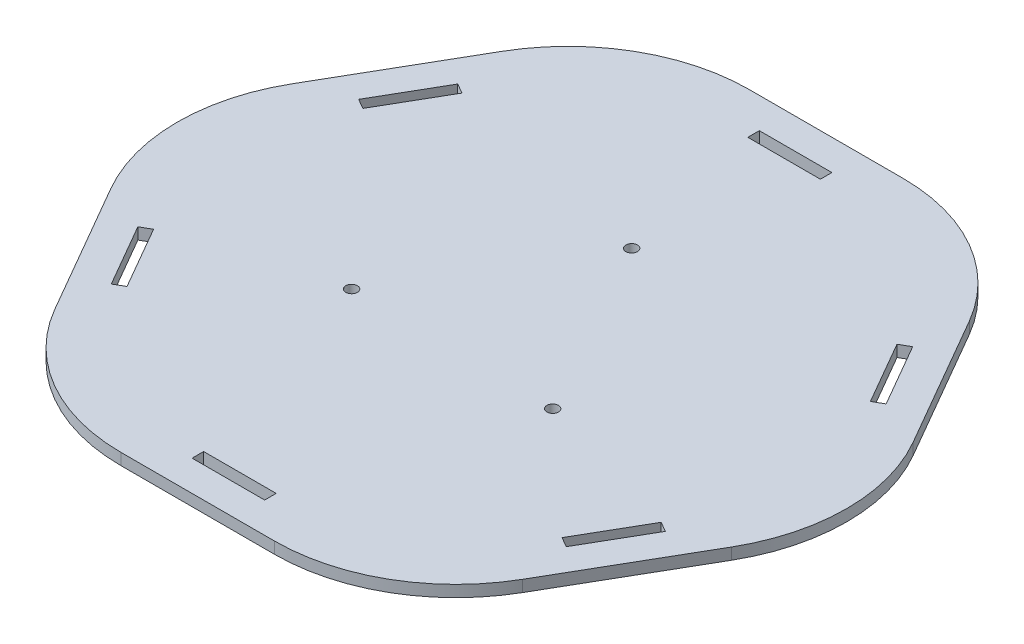
SolidWorks part; units mm, degrees
material "Acrylic (Medium-high impact)"
ref_plane "Front Plane" through (0, 0, 0) normal (0, 0, 1) x (1, 0, 0)
ref_plane "Top Plane" through (0, 0, 0) normal (0, 1, 0) x (1, 0, 0)
ref_plane "Right Plane" through (0, 0, 0) normal (1, 0, 0) x (0, 0, -1)
sketch "Sketch1" plane through (0, 0, 0) normal (0, 1, 0) x (1, 0, 0)
  line L0 (0, 0) -> (200, 0)
  line L1 (171.1325, 50) -> (128.8675, 123.2051)
  line L2 (42.265, 173.2051) -> (-42.265, 173.2051)
  line L3 (-128.8675, 123.2051) -> (-171.1325, 50)
  line L4 (-171.1325, -50) -> (-128.8675, -123.2051)
  line L5 (-42.265, -173.2051) -> (42.265, -173.2051)
  line L6 (128.8675, -123.2051) -> (171.1325, -50)
  line L8 (-20, -150) -> (20, -150)
  line L9 (-20, -150) -> (-20, -156.35)
  line L10 (-20, -156.35) -> (20, -156.35)
  line L11 (20, -150) -> (20, -156.35)
  line L12 (0, -55) -> (0, 55) construction
  line L13 (-55, 0) -> (55, 0) construction
  line L14 (-139.9038, -57.6795) -> (-145.4031, -60.8545)
  line L15 (-139.9038, -57.6795) -> (-119.9038, -92.3205)
  line L16 (-119.9038, -92.3205) -> (-125.4031, -95.4955)
  line L17 (-145.4031, -60.8545) -> (-125.4031, -95.4955)
  line L18 (-119.9038, 92.3205) -> (-125.4031, 95.4955)
  line L19 (-119.9038, 92.3205) -> (-139.9038, 57.6795)
  line L20 (-139.9038, 57.6795) -> (-145.4031, 60.8545)
  line L21 (-125.4031, 95.4955) -> (-145.4031, 60.8545)
  line L22 (20, 150) -> (20, 156.35)
  line L23 (20, 150) -> (-20, 150)
  line L24 (-20, 150) -> (-20, 156.35)
  line L25 (20, 156.35) -> (-20, 156.35)
  line L26 (139.9038, 57.6795) -> (145.4031, 60.8545)
  line L27 (139.9038, 57.6795) -> (119.9038, 92.3205)
  line L28 (119.9038, 92.3205) -> (125.4031, 95.4955)
  line L29 (145.4031, 60.8545) -> (125.4031, 95.4955)
  line L30 (119.9038, -92.3205) -> (125.4031, -95.4955)
  line L31 (119.9038, -92.3205) -> (139.9038, -57.6795)
  line L32 (139.9038, -57.6795) -> (145.4031, -60.8545)
  line L33 (125.4031, -95.4955) -> (145.4031, -60.8545)
  circle A0 centre (0, 0) radius 200 construction
  arc A25 (-42.265, 173.2051) -> (-128.8675, 123.2051) centre (-42.265, 73.2051) ccw
  arc A26 (-171.1325, 50) -> (-171.1325, -50) centre (-84.5299, 0) ccw
  arc A27 (-128.8675, -123.2051) -> (-42.265, -173.2051) centre (-42.265, -73.2051) ccw
  arc A28 (42.265, -173.2051) -> (128.8675, -123.2051) centre (42.265, -73.2051) ccw
  arc A29 (171.1325, -50) -> (171.1325, 50) centre (84.5299, 0) ccw
  arc A30 (128.8675, 123.2051) -> (42.265, 173.2051) centre (42.265, 73.2051) ccw
  point P43 (0, 0)
  point P88 (0, 0)
  point P94 (100, -173.2051)
  dimension "D1" = 400
  dimension "D7" = 6
  dimension "D20" = 100
  dimension "D2" = 200
  dimension "D3" = 40
  dimension "D4" = 20
  dimension "D5" = 6.35
  dimension "D6" = 150
extrude "Boss-Extrude1" add sketch "Sketch1" along normal blind 6.35
sketch "Sketch2" plane through (0, 6.35, 0) normal (0, 1, 0) x (1, 0, 0)
  line L0 (0, -1.1339) -> (85.0289, -1.1339)
  line L1 (0, -55) -> (0, 55) construction
  line L2 (55.7942, -33.3467) -> (0, -1.1339)
  circle A0 centre (55.7942, -33.3467) radius 3.2
  circle A1 centre (-56.7762, -31.6459) radius 3.2
  circle A2 centre (0.982, 64.9926) radius 3.2
  point P14 (0, 0)
  dimension "D3" = 6.4
  dimension "D1" = 65
  dimension "D2" = 30
  dimension "D4" = 3
extrude "Cut-Extrude1" cut sketch "Sketch2" against normal up to surface (6.35 mm away) contours A2 | A0 | A1 up to face at (0, 0, 0)
